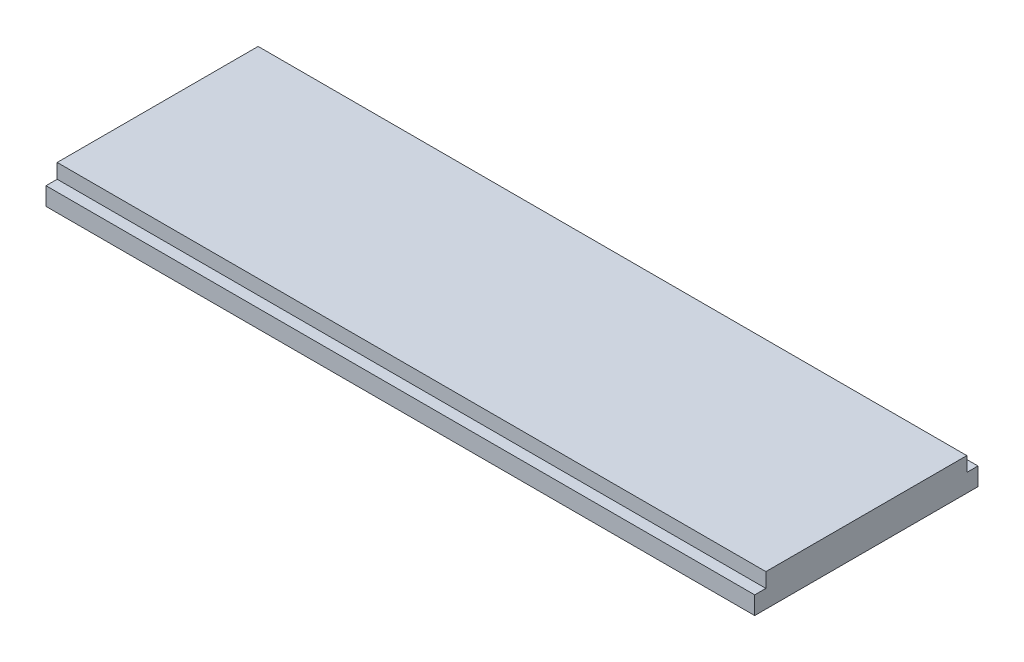
SolidWorks part; units mm, degrees
ref_plane "Front Plane" through (0, 0, 0) normal (0, 0, 1) x (1, 0, 0)
ref_plane "Top Plane" through (0, 0, 0) normal (0, 1, 0) x (1, 0, 0)
ref_plane "Right Plane" through (0, 0, 0) normal (1, 0, 0) x (0, 0, -1)
sketch "Sketch1" plane through (0, 0, 0) normal (0, 1, 0) x (1, 0, 0)
  line L1 (0, 0) -> (1460, 0)
  line L2 (0, 0) -> (0, 460)
  line L3 (0, 460) -> (1460, 460)
  line L4 (1460, 0) -> (1460, 460)
  dimension "D1" = 460
  dimension "D2" = 1460
extrude "Boss-Extrude1" add sketch "Sketch1" along normal blind 67
sketch "Sketch2" plane through (0, 67, 0) normal (0, 1, 0) x (1, 0, 0)
  line L0 (1460, 0) -> (1460, 460) construction
  line L1 (0, 0) -> (1460, 0)
  line L2 (0, 0) -> (0, 23)
  line L3 (0, 23) -> (1460, 23)
  line L4 (1460, 0) -> (1460, 23)
  line L5 (0, 230) -> (1509.6888, 230) construction
  line L6 (0, 460) -> (0, 0) construction
  line L7 (0, 437) -> (1460, 437)
  line L8 (1460, 460) -> (1460, 437)
  line L9 (0, 460) -> (1460, 460)
  line L10 (0, 460) -> (0, 437)
  dimension "D1" = 23
extrude "Cut-Extrude1" cut sketch "Sketch2" against normal blind 30
